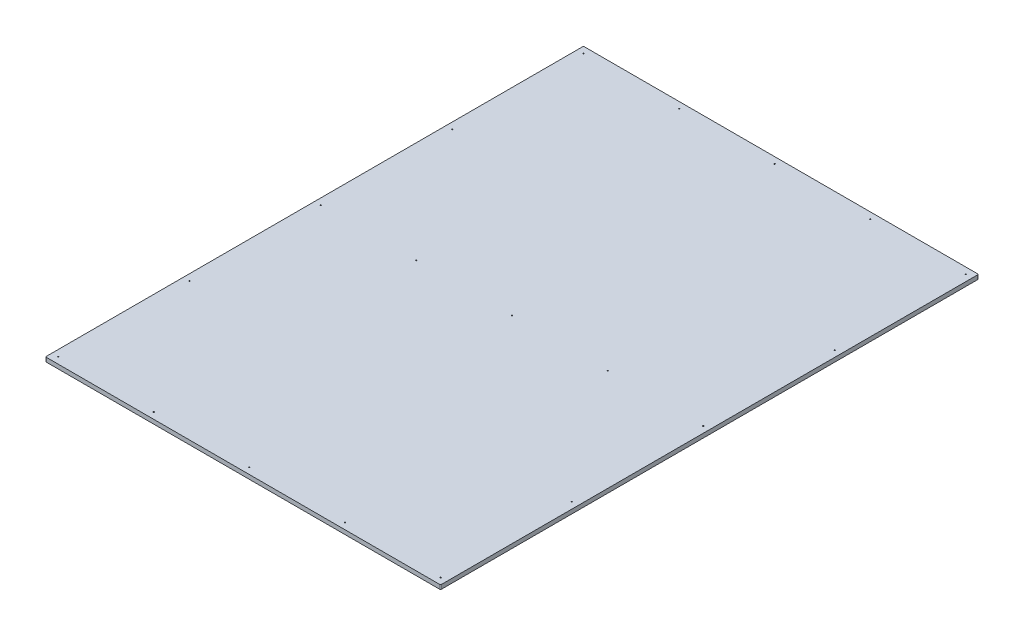
SolidWorks part; units mm, degrees
ref_plane "Front Plane" through (0, 0, 0) normal (0, 0, 1) x (1, 0, 0)
ref_plane "Top Plane" through (0, 0, 0) normal (0, 1, 0) x (1, 0, 0)
ref_plane "Right Plane" through (0, 0, 0) normal (1, 0, 0) x (0, 0, -1)
sketch "Sketch1" plane through (0, 0, 0) normal (0, 1, 0) x (1, 0, 0)
  line L1 (-596.9, -812.8) -> (596.9, -812.8)
  line L2 (-596.9, -812.8) -> (-596.9, 812.8)
  line L3 (-596.9, 812.8) -> (596.9, 812.8)
  line L4 (596.9, -812.8) -> (596.9, 812.8)
  line L5 (-596.9, -812.8) -> (596.9, 812.8) construction
  line L6 (-596.9, 812.8) -> (596.9, -812.8) construction
  point P0 (0, 0)
  dimension "D1" = 1193.8
  dimension "D2" = 1625.6
extrude "Boss-Extrude1" add sketch "Sketch1" along normal blind 12.7
hole_wizard "1/8 (0.125) Diameter Hole1" positions "Sketch2" profile "Sketch3" hole size "1/8" standard "ANSI Inch" end condition up to next
sketch "Sketch2" plane through (0, 12.7, 0) normal (0, 1, 0) x (1, 0, 0)
  line L1 (-596.9, -812.8) -> (596.9, -812.8) construction
  line L2 (-596.9, 812.8) -> (-596.9, -812.8) construction
  line L3 (596.9, 812.8) -> (-596.9, 812.8) construction
  line L4 (596.9, -812.8) -> (596.9, 812.8) construction
  line L5 (-596.9, -812.8) -> (596.9, -812.8) construction
  line L6 (-596.9, 812.8) -> (-596.9, -812.8) construction
  line L7 (596.9, 812.8) -> (-596.9, 812.8) construction
  line L8 (596.9, -812.8) -> (596.9, 812.8) construction
  line L9 (-577.85, -793.75) -> (577.85, -793.75) construction
  line L10 (577.85, -793.75) -> (577.85, 793.75) construction
  line L11 (577.85, 793.75) -> (-577.85, 793.75) construction
  line L12 (-577.85, 793.75) -> (-577.85, -793.75) construction
  point P35 (-577.85, -793.75)
  point P38 (-577.85, 793.75)
  point P55 (-288.925, 793.75)
  point P56 (0, 793.75)
  point P57 (288.925, 793.75)
  point P58 (577.85, 793.75)
  point P65 (-288.925, -793.75)
  point P66 (0, -793.75)
  point P67 (288.925, -793.75)
  point P68 (577.85, -793.75)
  point P72 (-577.85, 0)
  point P79 (-288.925, 0)
  point P80 (0, 0)
  point P81 (288.925, 0)
  point P82 (577.85, 0)
  dimension "D2" = 5
  dimension "D1" = 19.05
sketch "Sketch3" plane through (577.85, 12.7, 0) normal (1, 0, 0) x (0, 0, 1)
  line L0 (0, 0) -> (0, 12.7)
  line L1 (0, 12.7) -> (1.5875, 12.7)
  line L2 (1.5875, 12.7) -> (1.5875, 0)
  line L5 (1.5875, 0) -> (0, 0)
  line L11 (0, -6.35) -> (0, 107.95) construction
  dimension "Thru Hole Dia." = 3.175
  dimension "Thru Hole Depth" = 12.7
hole_wizard "1/8 (0.125) Diameter Hole2" positions "Sketch4" profile "Sketch5" hole size "1/8" standard "ANSI Inch" end condition up to next
sketch "Sketch4" plane through (0, 12.7, 0) normal (0, 1, 0) x (1, 0, 0)
  line L0 (-577.85, 812.8) -> (-577.85, -812.8) construction
  line L1 (596.9, 812.8) -> (-596.9, 812.8) construction
  line L2 (-596.9, -812.8) -> (596.9, -812.8) construction
  line L4 (-596.9, 812.8) -> (-596.9, -812.8) construction
  line L5 (-596.9, -793.75) -> (596.9, -793.75) construction
  line L6 (596.9, -812.8) -> (596.9, 812.8) construction
  line L7 (577.85, 812.8) -> (577.85, -812.8) construction
  point P16 (-577.85, -396.875)
  point P22 (-577.85, -793.75)
  point P24 (577.85, -793.75)
  point P32 (-577.85, -396.875)
  point P33 (577.85, -396.875)
  point P34 (-577.85, 0)
  point P35 (577.85, 0)
  point P36 (-577.85, 396.875)
  point P37 (577.85, 396.875)
  dimension "D1" = 19.05
  dimension "D2" = 19.05
  dimension "D3" = 19.05
  dimension "D4" = 4
sketch "Sketch5" plane through (577.85, 12.7, -396.875) normal (1, 0, 0) x (0, 0, 1)
  line L0 (0, 0) -> (0, 12.7)
  line L1 (0, 12.7) -> (1.5875, 12.7)
  line L2 (1.5875, 12.7) -> (1.5875, 0)
  line L5 (1.5875, 0) -> (0, 0)
  line L11 (0, -6.35) -> (0, 107.95) construction
  dimension "Thru Hole Dia." = 3.175
  dimension "Thru Hole Depth" = 12.7
fillet "Fillet1" radius 2.54 4 edges at (596.9, 6.35, -812.8) (-596.9, 6.35, -812.8) (-596.9, 6.35, 812.8) (596.9, 6.35, 812.8)
